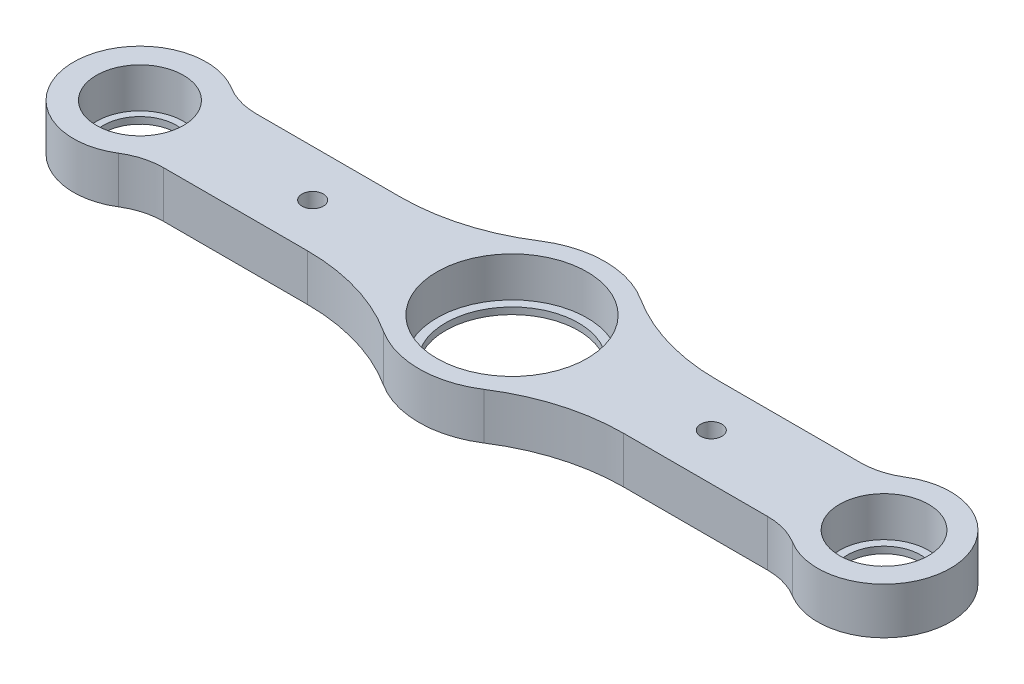
SolidWorks part; units mm, degrees
ref_plane "Front" through (0, 0, 0) normal (0, 0, 1) x (1, 0, 0)
ref_plane "Top" through (0, 0, 0) normal (0, 1, 0) x (1, 0, 0)
ref_plane "Right" through (0, 0, 0) normal (1, 0, 0) x (0, 0, -1)
sketch "Эскиз1" plane through (0, 0, 0) normal (0, 1, 0) x (1, 0, 0)
  line L5 (0, 22.0555) -> (0, -18.1771) construction
  line L6 (53, 14) -> (53, -14) construction
  line L21 (-23.8118, 7) -> (-45.4643, 7)
  line L22 (-23.8118, -7) -> (-45.4643, -7)
  line L25 (45.4643, 7) -> (23.8118, 7)
  line L26 (45.4643, -7) -> (23.8118, -7)
  circle A0 centre (0, 0) radius 10
  circle A2 centre (56, 0) radius 5.5
  circle A16 centre (-56, 0) radius 5.5
  arc A23 (-7.5765, -11.7727) -> (7.5765, -11.7727) centre (0, 0) ccw
  arc A24 (7.5765, 11.7727) -> (-7.5765, 11.7727) centre (0, 0) ccw
  arc A25 (7.5765, 11.7727) -> (23.8118, 7) centre (23.8118, 37) ccw
  arc A28 (7.5765, -11.7727) -> (23.8118, -7) centre (23.8118, -37) cw
  arc A29 (-23.8118, 7) -> (-7.5765, 11.7727) centre (-23.8118, 37) ccw
  arc A30 (-23.8118, -7) -> (-7.5765, -11.7727) centre (-23.8118, -37) cw
  circle A34 centre (-30, 0) radius 1.6
  circle A35 centre (30, 0) radius 1.6
  arc A36 (-50.7322, 8.5) -> (-50.7322, -8.5) centre (-56, 0) ccw
  arc A37 (50.7322, -8.5) -> (50.7322, 8.5) centre (56, 0) ccw
  arc A38 (45.4643, -7) -> (50.7322, -8.5) centre (45.4643, -17) cw
  arc A39 (45.4643, 7) -> (50.7322, 8.5) centre (45.4643, 17) ccw
  arc A40 (-45.4643, -7) -> (-50.7322, -8.5) centre (-45.4643, -17) ccw
  arc A41 (-45.4643, 7) -> (-50.7322, 8.5) centre (-45.4643, 17) cw
  point P1 (0, -14)
  point P6 (0, 14)
  point P10 (12.1244, 7)
  point P37 (4.3617, -13.3032)
  dimension "D1" = 30
  dimension "D2" = 112
  dimension "D3" = 10
extrude "Бобышка-Вытянуть1" add sketch "Эскиз1" along normal blind 7
sketch "Эскиз3" plane through (0, 7, 0) normal (0, 1, 0) x (1, 0, 0)
  circle A0 centre (-56, 0) radius 6.55
  circle A1 centre (56, 0) radius 6.7
extrude "Вырез-Вытянуть1" cut sketch "Эскиз3" against normal blind 6
sketch "Эскиз4" plane through (0, 7, 0) normal (0, 1, 0) x (1, 0, 0)
  circle A0 centre (0, 0) radius 11.3
extrude "Вырез-Вытянуть2" cut sketch "Эскиз4" against normal blind 6
